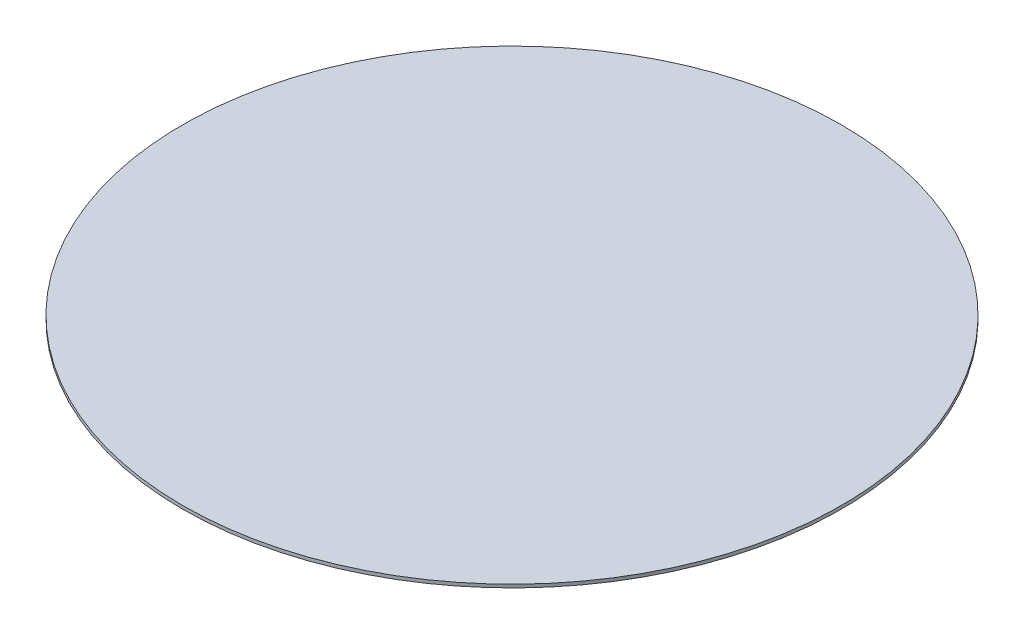
SolidWorks part; units mm, degrees
ref_plane "Front Plane" through (0, 0, 0) normal (0, 0, 1) x (1, 0, 0)
ref_plane "Top Plane" through (0, 0, 0) normal (0, 1, 0) x (1, 0, 0)
ref_plane "Right Plane" through (0, 0, 0) normal (1, 0, 0) x (0, 0, -1)
sketch "Sketch2" plane through (0, 0, 0) normal (0, 1, 0) x (1, 0, 0)
  circle A0 centre (0, 0) radius 609.6
extrude "Boss-Extrude1" add sketch "Sketch2" along normal blind 6
